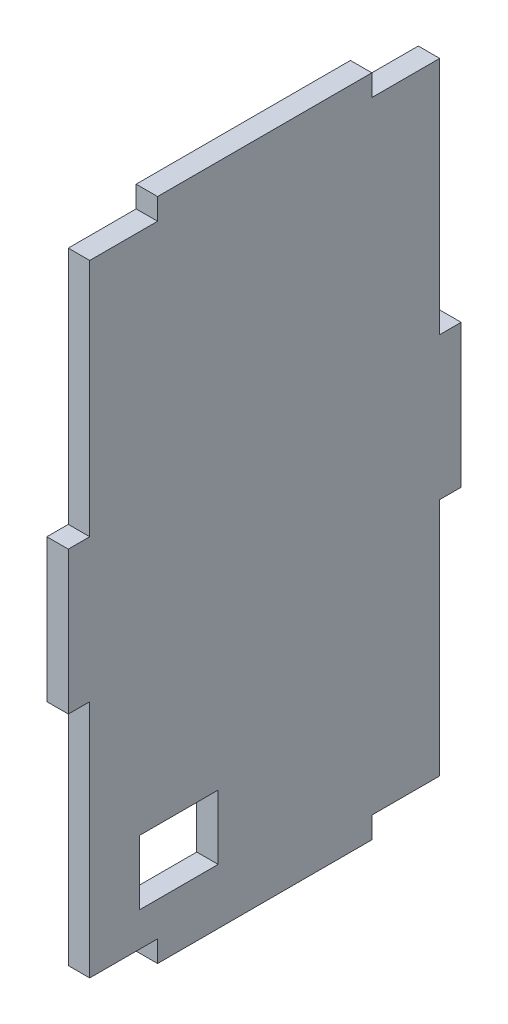
SolidWorks part; units mm, degrees
ref_plane "Front Plane" through (0, 0, 0) normal (0, 0, 1) x (1, 0, 0)
ref_plane "Top Plane" through (0, 0, 0) normal (0, 1, 0) x (1, 0, 0)
ref_plane "Right Plane" through (0, 0, 0) normal (1, 0, 0) x (0, 0, -1)
sketch "Sketch2" plane through (0, 0, 0) normal (1, 0, 0) x (0, 0, -1)
  line L1 (-27.5, 46.5) -> (27.5, 46.5)
  line L2 (-27.5, 46.5) -> (-27.5, -46.5)
  line L3 (-27.5, -46.5) -> (27.5, -46.5)
  line L4 (27.5, 46.5) -> (27.5, -46.5)
  line L5 (-27.5, 46.5) -> (27.5, -46.5) construction
  line L6 (-27.5, -46.5) -> (27.5, 46.5) construction
  point P0 (0, 0)
  dimension "D1" = 93
  dimension "D2" = 55
extrude "Boss-Extrude1" add sketch "Sketch2" along normal blind 3
sketch "Sketch3" plane through (3, 0, 0) normal (1, 0, 0) x (0, 0, -1)
  line L0 (0, 46.5) -> (0, -46.5) construction
  line L1 (-27.5, 46.5) -> (-24.5, 46.5)
  line L2 (-27.5, 46.5) -> (-27.5, 10)
  line L3 (-27.5, 10) -> (-24.5, 10)
  line L4 (-24.5, 43.5) -> (-24.5, 10)
  line L5 (-24.5, 46.5) -> (-15, 46.5)
  line L7 (-24.5, 43.5) -> (-15, 43.5)
  line L8 (-15, 46.5) -> (-15, 43.5)
  line L9 (27.5, 46.5) -> (-27.5, 46.5) construction
  line L10 (-27.5, -46.5) -> (27.5, -46.5) construction
  line L11 (-27.5, 0) -> (27.5, 0) construction
  line L12 (-27.5, 46.5) -> (-27.5, -46.5) construction
  line L13 (27.5, -46.5) -> (27.5, 46.5) construction
  line L14 (27.5, 46.5) -> (27.5, 10)
  line L15 (27.5, 10) -> (24.5, 10)
  line L16 (24.5, 43.5) -> (24.5, 10)
  line L17 (24.5, 43.5) -> (15, 43.5)
  line L18 (15, 46.5) -> (15, 43.5)
  line L19 (24.5, 46.5) -> (15, 46.5)
  line L20 (27.5, 46.5) -> (24.5, 46.5)
  line L21 (27.5, -46.5) -> (24.5, -46.5)
  line L22 (24.5, -46.5) -> (15, -46.5)
  line L23 (15, -46.5) -> (15, -43.5)
  line L24 (24.5, -43.5) -> (15, -43.5)
  line L25 (24.5, -43.5) -> (24.5, -10)
  line L26 (27.5, -10) -> (24.5, -10)
  line L27 (27.5, -46.5) -> (27.5, -10)
  line L28 (-27.5, -46.5) -> (-27.5, -10)
  line L29 (-27.5, -10) -> (-24.5, -10)
  line L30 (-24.5, -43.5) -> (-24.5, -10)
  line L31 (-24.5, -43.5) -> (-15, -43.5)
  line L32 (-15, -46.5) -> (-15, -43.5)
  line L33 (-24.5, -46.5) -> (-15, -46.5)
  line L34 (-27.5, -46.5) -> (-24.5, -46.5)
  line L36 (-6.5152, -38.7191) -> (-17.5129, -38.7191)
  line L37 (-6.5152, -38.7191) -> (-6.5152, -29.7023)
  line L38 (-6.5152, -29.7023) -> (-17.5129, -29.7023)
  line L39 (-17.5129, -38.7191) -> (-17.5129, -29.7023)
  dimension "D1" = 36.5
  dimension "D2" = 3
  dimension "D3" = 3
  dimension "D4" = 9.5
  dimension "D5" = 33.5
  dimension "D6" = 10.9977
  dimension "D7" = 9.0168
  dimension "D8" = 6.9871
  dimension "D9" = 4.7809
extrude "Cut-Extrude1" cut sketch "Sketch3" against normal blind 3
